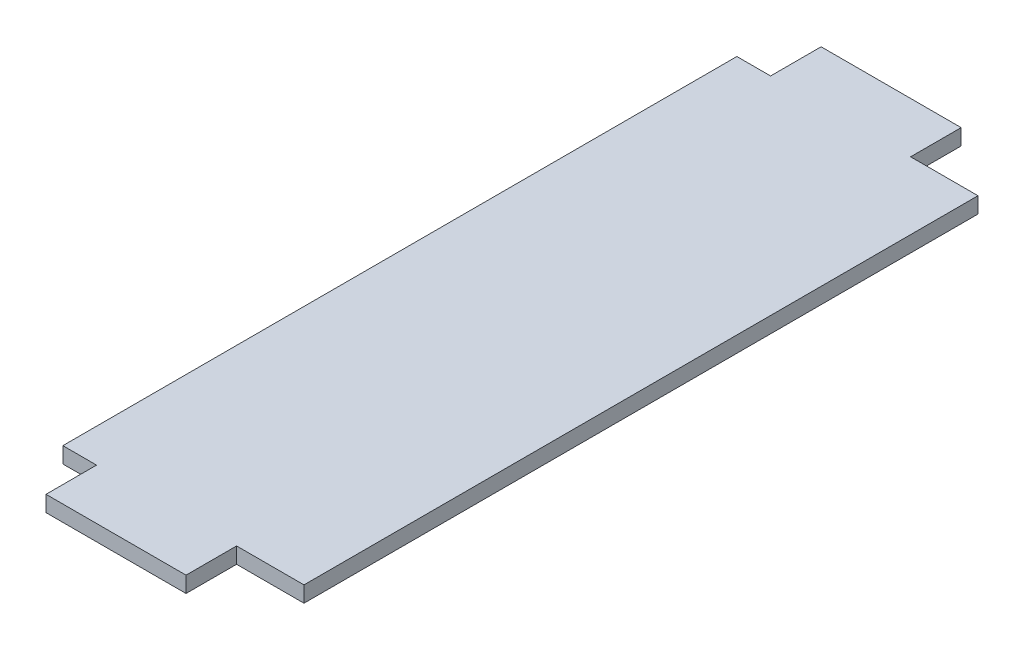
SolidWorks part; units mm, degrees
ref_plane "Front Plane" through (0, 0, 0) normal (0, 0, 1) x (1, 0, 0)
ref_plane "Top Plane" through (0, 0, 0) normal (0, 1, 0) x (1, 0, 0)
ref_plane "Right Plane" through (0, 0, 0) normal (1, 0, 0) x (0, 0, -1)
sketch "Sketch1" plane through (0, 0, 0) normal (0, 1, 0) x (1, 0, 0)
  line L0 (-22.7168, 66.4972) -> (22.7168, 66.4972) construction
  line L1 (22.7168, -73.025) -> (-22.7168, -73.025)
  line L2 (22.7168, -73.025) -> (22.7168, 73.025)
  line L3 (22.7168, 73.025) -> (-22.7168, 73.025)
  line L4 (-22.7168, -73.025) -> (-22.7168, 73.025)
  line L5 (22.7168, -73.025) -> (-22.7168, 73.025) construction
  line L6 (22.7168, 73.025) -> (-22.7168, -73.025) construction
  line L7 (-22.7168, -66.4972) -> (22.7168, -66.4972) construction
  line L8 (-22.7168, 66.4972) -> (-22.7168, -66.4972) construction
  line L9 (22.7168, 66.4972) -> (22.7168, -66.4972) construction
  line L20 (-22.7168, -73.025) -> (-16.3668, -73.025)
  line L21 (-22.7168, -73.025) -> (-22.7168, -63.5)
  line L22 (-22.7168, -63.5) -> (-16.3668, -63.5)
  line L23 (-16.3668, -73.025) -> (-16.3668, -63.5)
  line L24 (22.7168, -73.025) -> (10.0168, -73.025)
  line L25 (22.7168, -73.025) -> (22.7168, -63.5)
  line L26 (22.7168, -63.5) -> (10.0168, -63.5)
  line L27 (10.0168, -73.025) -> (10.0168, -63.5)
  line L28 (-22.7168, 73.025) -> (-16.3668, 73.025)
  line L29 (-22.7168, 73.025) -> (-22.7168, 63.5)
  line L30 (-22.7168, 63.5) -> (-16.3668, 63.5)
  line L31 (-16.3668, 73.025) -> (-16.3668, 63.5)
  line L32 (22.7168, 73.025) -> (10.0168, 73.025)
  line L33 (22.7168, 73.025) -> (22.7168, 63.5)
  line L34 (22.7168, 63.5) -> (10.0168, 63.5)
  line L35 (10.0168, 73.025) -> (10.0168, 63.5)
  point P0 (0, 0)
  point P10 (22.7168, 0)
  point P11 (22.7168, 0)
  point P24 (9.8601, -57.5554)
  point P25 (6.6267, 58.445)
  dimension "D1" = 45.4337
  dimension "D2" = 146.05
  dimension "D3" = 132.9944
  dimension "D4" = 6.35
  dimension "D5" = 12.7
  dimension "D6" = 127
extrude "Boss-Extrude1" add sketch "Sketch1" along normal blind 2.9972
